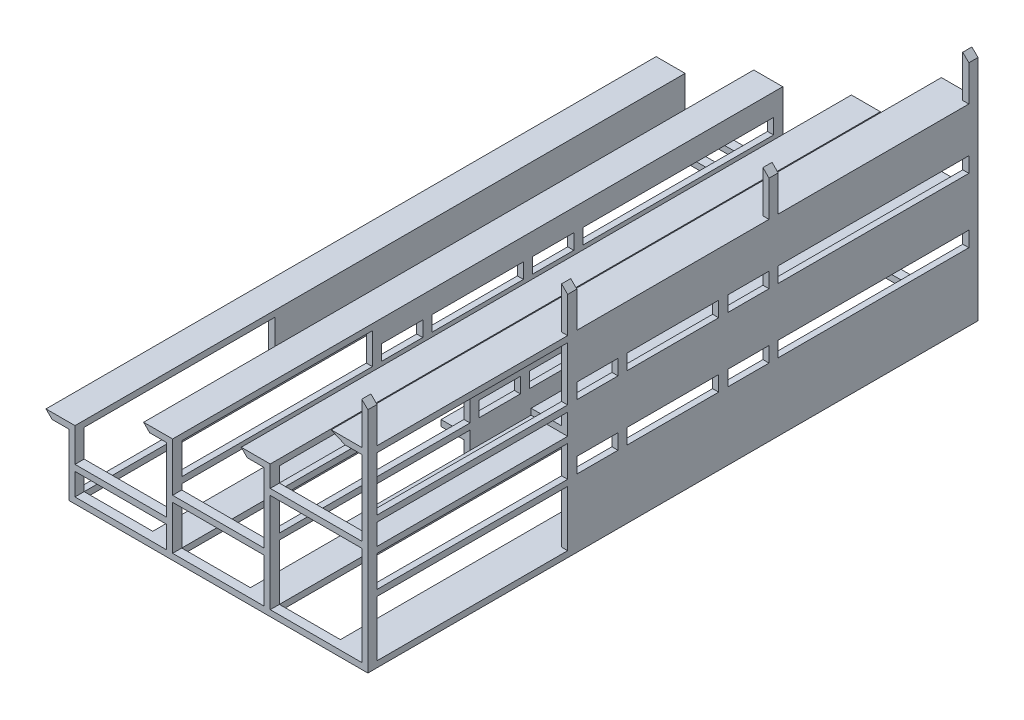
SolidWorks part; units mm, degrees
ref_plane "Plan de face" through (0, 0, 0) normal (0, 0, 1) x (1, 0, 0)
ref_plane "Plan de dessus" through (0, 0, 0) normal (0, 1, 0) x (1, 0, 0)
ref_plane "Plan de droite" through (0, 0, 0) normal (1, 0, 0) x (0, 0, -1)
sketch "Esquisse1" plane through (0, 0, 0) normal (0, 0, 1) x (1, 0, 0)
  line L1 (0, 0) -> (2110, 0)
  line L2 (0, 0) -> (0, 1535)
  line L3 (0, 1535) -> (2110, 1535)
  line L4 (2110, 0) -> (2110, 1535)
  dimension "D1" = 1535
  dimension "D2" = 2110
extrude "Boss.-Extru.1" add sketch "Esquisse1" along normal blind 4000
sketch "Esquisse2" plane through (0, 0, 0) normal (0, 0, 1) x (1, 0, 0)
  line L1 (190, 225) -> (790, 225)
  line L3 (790, 225) -> (790, 649.1451)
  line L5 (150, 0) -> (150, 405)
  line L11 (0, 0) -> (2110, 0) construction
  line L12 (150, 405) -> (40, 405)
  line L13 (40, 405) -> (0, 445)
  line L14 (0, 445) -> (190, 445)
  line L15 (190, 445) -> (190, 225)
  line L16 (790, 649.1451) -> (680, 649.1451)
  line L17 (680, 649.1451) -> (640, 689.1451)
  line L18 (640, 689.1451) -> (830, 689.1451)
  line L19 (830, 689.1451) -> (830, 369.419)
  line L20 (830, 369.419) -> (1430, 369.419)
  line L21 (1430, 369.419) -> (1430, 827.1365)
  line L22 (1430, 827.1365) -> (1320, 827.1365)
  line L23 (1320, 827.1365) -> (1280, 867.1365)
  line L24 (1280, 867.1365) -> (1470, 867.1365)
  line L25 (1470, 867.1365) -> (1470, 728.6673)
  line L26 (1470, 728.6673) -> (2070, 728.6673)
  line L27 (2070, 728.6673) -> (2070, 1221.0021)
  line L28 (2070, 1221.0021) -> (1960, 1221.0021)
  line L29 (1960, 1221.0021) -> (1870, 1261.0021)
  line L30 (1870, 1261.0021) -> (2070, 1261.0021)
  line L31 (2070, 1261.0021) -> (2070, 1535)
  line L32 (2110, 1535) -> (0, 1535) construction
  line L33 (2070, 1535) -> (2110, 1495)
  line L34 (2110, 0) -> (2110, 1535) construction
  line L35 (2110, 1495) -> (2110, 0)
  line L36 (2110, 0) -> (150, 0)
  line L38 (830, 329.419) -> (1430, 329.419)
  line L39 (830, 329.419) -> (830, 40)
  line L40 (830, 40) -> (1430, 40)
  line L41 (1430, 329.419) -> (1430, 40)
  line L43 (190, 185) -> (790, 185)
  line L44 (190, 185) -> (190, 40)
  line L45 (190, 40) -> (790, 40)
  line L46 (790, 185) -> (790, 40)
  line L51 (0, 1535) -> (0, 0) construction
  line L53 (1470, 688.6673) -> (2070, 688.6673)
  line L54 (1470, 688.6673) -> (1470, 40)
  line L55 (1470, 40) -> (2070, 40)
  line L56 (2070, 688.6673) -> (2070, 40)
  dimension "D3" = 40
  dimension "D4" = 40
  dimension "D5" = 225
  dimension "D6" = 445
  dimension "D7" = 190
  dimension "D8" = 110
  dimension "D9" = 40
  dimension "D10" = 600
  dimension "D11" = 0
  dimension "D12" = 600
  dimension "D13" = 40
  dimension "D14" = 40
  dimension "D15" = 190
  dimension "D16" = 110
  dimension "D17" = 40
  dimension "D18" = 40
  dimension "D19" = 200
  dimension "D20" = 110
  dimension "D21" = 40
  dimension "D22" = 40
  dimension "D23" = 40
  dimension "D24" = 40
  dimension "D25" = 40
  dimension "D26" = 40
  dimension "D27" = 40
  dimension "D28" = 600
  dimension "D29" = 40
  dimension "D30" = 40
  dimension "D31" = 40
  dimension "D32" = 40
  dimension "D33" = 40
  dimension "D34" = 40
extrude "Enlèv. mat.-Extru.1" cut sketch "Esquisse2" along direction (0, 0, -1) on the side of the normal through all flip side to cut
sketch "Esquisse3" plane through (0, 0, 0) normal (1, 0, 0) x (0, 0, -1)
  line L0 (-4000, 689.1451) -> (0, 689.1451) construction
  line L45 (-2690, 826.6297) -> (-3940, 826.6297)
  line L57 (-4000, 445) -> (0, 445) construction
  line L59 (-60, 445) -> (-1310, 445)
  line L60 (-60, 445) -> (-60, 545)
  line L61 (-60, 545) -> (-1310, 545)
  line L62 (-1310, 445) -> (-1310, 545)
  line L64 (-1370, 445) -> (-1640, 445)
  line L65 (-1370, 445) -> (-1370, 545)
  line L66 (-1370, 545) -> (-1640, 545)
  line L67 (-1640, 445) -> (-1640, 545)
  line L68 (-4000, 867.1365) -> (0, 867.1365) construction
  line L69 (-1700, 445) -> (-2300, 445)
  line L70 (-1700, 445) -> (-1700, 545)
  line L71 (-1700, 545) -> (-2300, 545)
  line L72 (-2300, 445) -> (-2300, 545)
  line L73 (-2360, 445) -> (-2630, 445)
  line L74 (-2360, 445) -> (-2360, 545)
  line L75 (-2360, 545) -> (-2630, 545)
  line L76 (-2630, 445) -> (-2630, 545)
  line L81 (-60, 867.1365) -> (-1310, 867.1365)
  line L82 (-60, 867.1365) -> (-60, 967.1365)
  line L83 (-60, 967.1365) -> (-1310, 967.1365)
  line L84 (-1310, 867.1365) -> (-1310, 967.1365)
  line L85 (-4000, 1261.0021) -> (0, 1261.0021) construction
  line L86 (-1370, 867.1365) -> (-1640, 867.1365)
  line L87 (-1370, 867.1365) -> (-1370, 967.1365)
  line L88 (-1370, 967.1365) -> (-1640, 967.1365)
  line L89 (-1640, 867.1365) -> (-1640, 967.1365)
  line L90 (-1700, 867.1365) -> (-2300, 867.1365)
  line L91 (-1700, 867.1365) -> (-1700, 967.1365)
  line L92 (-1700, 967.1365) -> (-2300, 967.1365)
  line L93 (-2300, 867.1365) -> (-2300, 967.1365)
  line L94 (-2360, 867.1365) -> (-2630, 867.1365)
  line L95 (-2360, 867.1365) -> (-2360, 967.1365)
  line L96 (-2360, 967.1365) -> (-2630, 967.1365)
  line L97 (-2630, 867.1365) -> (-2630, 967.1365)
  line L98 (-2690, 867.1365) -> (-3940, 867.1365)
  line L99 (-2690, 867.1365) -> (-2690, 1221.0021)
  line L100 (-2690, 1221.0021) -> (-3940, 1221.0021)
  line L101 (-3940, 867.1365) -> (-3940, 1221.0021)
  line L102 (-60, 1261.0021) -> (-1310, 1261.0021)
  line L103 (-60, 1261.0021) -> (-60, 1651.0021)
  line L104 (-60, 1651.0021) -> (-1310, 1651.0021)
  line L105 (-1310, 1261.0021) -> (-1310, 1651.0021)
  line L106 (-4000, 1261.0021) -> (0, 1261.0021) construction
  line L108 (-1370, 1261.0021) -> (-1370, 1651.0021)
  line L111 (-4000, 0) -> (0, 0) construction
  line L119 (-2630, 1261.0021) -> (-2630, 1651.0021)
  line L120 (-2690, 1261.0021) -> (-3940, 1261.0021)
  line L121 (-2690, 1261.0021) -> (-2690, 1751.0021)
  line L122 (-2690, 1751.0021) -> (-3940, 1751.0021)
  line L123 (-3940, 1261.0021) -> (-3940, 1751.0021)
  line L124 (-3940, 405) -> (-2690, 405)
  line L125 (-1370, 1651.0021) -> (-2630, 1651.0021)
  line L126 (-2630, 1261.0021) -> (-1370, 1261.0021)
  line L127 (-3940, 405) -> (-3940, 40)
  line L128 (-3940, 40) -> (-2690, 40)
  line L129 (-2690, 405) -> (-2690, 40)
  line L130 (-4000, 0) -> (-4000, 1495) construction
  line L131 (-2690, 826.6297) -> (-2690, 689.1451)
  line L136 (-2690, 689.1451) -> (-3940, 689.1451)
  line L137 (-3940, 826.6297) -> (-3940, 689.1451)
  line L138 (-4000, 649.1451) -> (0, 649.1451) construction
  line L139 (-2690, 649.1451) -> (-3940, 649.1451)
  line L140 (-2690, 649.1451) -> (-2690, 445)
  line L141 (-2690, 445) -> (-3940, 445)
  line L142 (-3940, 649.1451) -> (-3940, 445)
  line L143 (-4000, 405) -> (0, 405) construction
  dimension "D3" = 40
  dimension "D4" = 60
  dimension "D5" = 40
  dimension "D17" = 100
  dimension "D18" = 100
  dimension "D19" = 390
  dimension "D20" = 100
  dimension "D21" = 100
  dimension "D22" = 100
  dimension "D23" = 490
  dimension "D24" = 100
  dimension "D25" = 100
  dimension "D26" = 100
extrude "Enlèv. mat.-Extru.11" cut sketch "Esquisse3" along normal blind 4000
sketch "Esquisse4" plane through (0, 0, 0) normal (0, 1, 0) x (1, 0, 0)
  line L0 (190, -4000) -> (190, 0) construction
  line L1 (190, -60) -> (640, -60)
  line L2 (190, -60) -> (190, -3940)
  line L3 (190, -3940) -> (640, -3940)
  line L4 (640, -60) -> (640, -3940)
  line L5 (640, -4000) -> (640, 0) construction
  line L6 (790, 0) -> (190, 0) construction
  line L7 (790, -4000) -> (190, -4000) construction
  line L8 (830, -2690) -> (830, 0) construction
  line L9 (830, -60) -> (1280, -60)
  line L10 (830, -60) -> (830, -3940)
  line L11 (830, -3940) -> (1280, -3940)
  line L12 (1280, -60) -> (1280, -3940)
  line L13 (1280, -4000) -> (1280, 0) construction
  line L14 (1470, -2690) -> (1470, 0) construction
  line L15 (1470, -60) -> (1870, -60)
  line L16 (1470, -60) -> (1470, -3940)
  line L17 (1470, -3940) -> (1870, -3940)
  line L18 (1870, -60) -> (1870, -3940)
  line L19 (1870, -4000) -> (1870, 0) construction
  line L20 (1430, 0) -> (830, 0) construction
  line L21 (2070, 0) -> (1470, 0) construction
  line L22 (1430, -4000) -> (830, -4000) construction
  line L23 (2070, -4000) -> (1470, -4000) construction
  dimension "D1" = 60
  dimension "D2" = 60
  dimension "D3" = 60
  dimension "D4" = 60
  dimension "D5" = 60
  dimension "D6" = 60
extrude "Enlèv. mat.-Extru.13" cut sketch "Esquisse4" along normal blind 1800
